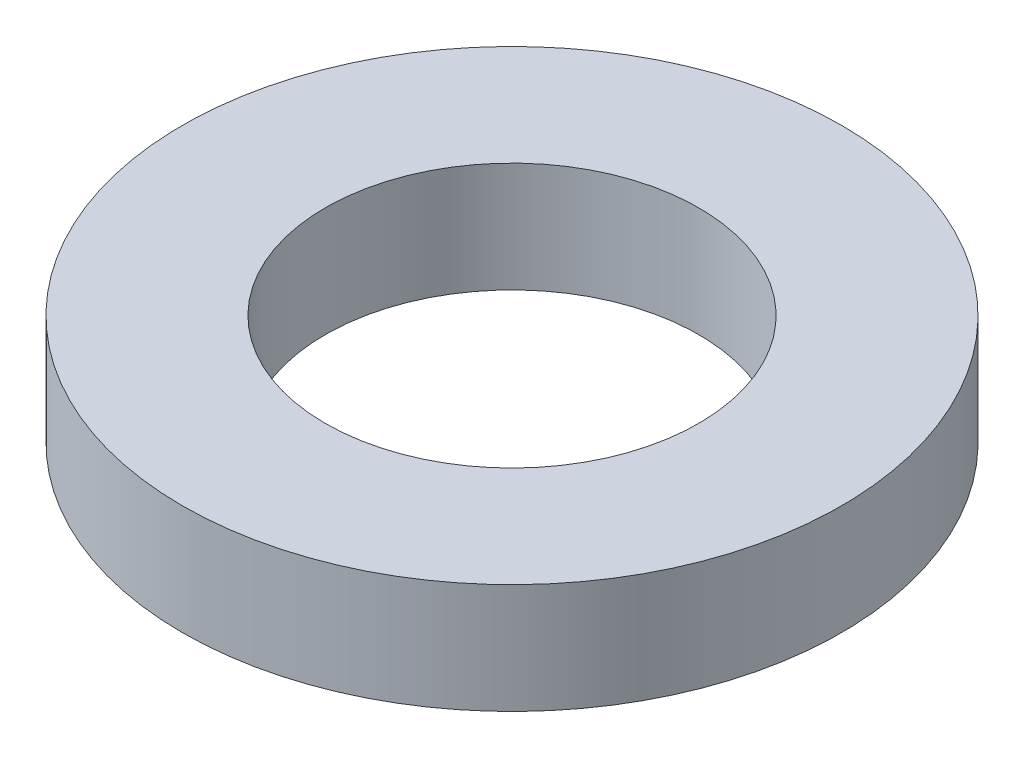
SolidWorks part; units mm, degrees
ref_plane "Front Plane" through (0, 0, 0) normal (0, 0, 1) x (1, 0, 0)
ref_plane "Top Plane" through (0, 0, 0) normal (0, 1, 0) x (1, 0, 0)
ref_plane "Right Plane" through (0, 0, 0) normal (1, 0, 0) x (0, 0, -1)
sketch "Sketch1" plane through (0, 0, 0) normal (0, 1, 0) x (1, 0, 0)
  circle A0 centre (0, 0) radius 4.5
  circle A1 centre (0, 0) radius 2.55
  dimension "D1" = 9
  dimension "D2" = 5.1
extrude "Boss-Extrude1" add sketch "Sketch1" along normal blind 1.5
equation "\"D_OUT\"= 9"
equation "\"D1@Sketch1\"=\"D_OUT\""
equation "\"D_IN\"= 5 + \"IN_TOL\""
equation "\"D2@Sketch1\"=\"D_IN\""
equation "\"THICK\"= 1.5"
equation "\"D1@Boss-Extrude1\"=\"THICK\""
equation "\"IN_TOL\"= 0.1"
